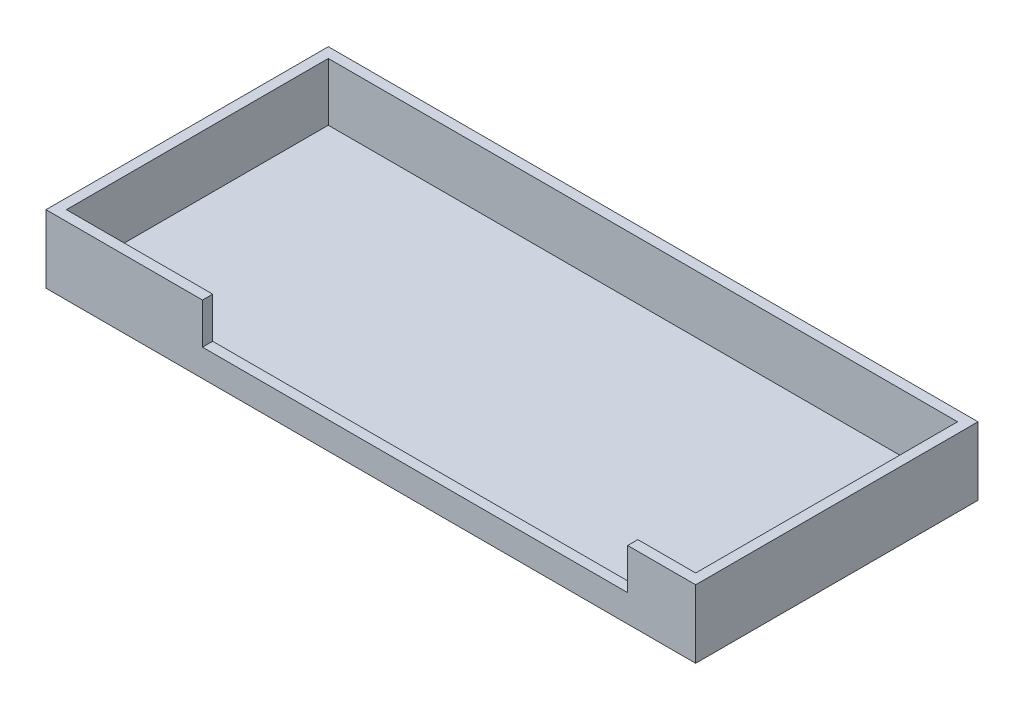
SolidWorks part; units mm, degrees
ref_plane "Front Plane" through (0, 0, 0) normal (0, 0, 1) x (1, 0, 0)
ref_plane "Top Plane" through (0, 0, 0) normal (0, 1, 0) x (1, 0, 0)
ref_plane "Right Plane" through (0, 0, 0) normal (1, 0, 0) x (0, 0, -1)
sketch "Sketch1" plane through (0, 0, 0) normal (0, 1, 0) x (1, 0, 0)
  line L1 (95.5, 41.5) -> (-95.5, 41.5)
  line L2 (95.5, 41.5) -> (95.5, -41.5)
  line L3 (95.5, -41.5) -> (-95.5, -41.5)
  line L4 (-95.5, 41.5) -> (-95.5, -41.5)
  line L5 (95.5, 41.5) -> (-95.5, -41.5) construction
  line L6 (95.5, -41.5) -> (-95.5, 41.5) construction
  point P0 (0, 0)
  dimension "D1" = 191
  dimension "D2" = 83
extrude "Boss-Extrude2" add sketch "Sketch1" along normal blind 20
sketch "Sketch3" plane through (0, 20, 0) normal (0, 1, 0) x (1, 0, 0)
  line L1 (92.5, 38.5) -> (-92.5, 38.5)
  line L2 (92.5, 38.5) -> (92.5, -38.5)
  line L3 (92.5, -38.5) -> (-92.5, -38.5)
  line L4 (-92.5, 38.5) -> (-92.5, -38.5)
  line L5 (92.5, 38.5) -> (-92.5, -38.5) construction
  line L6 (92.5, -38.5) -> (-92.5, 38.5) construction
  point P0 (0, 0)
  dimension "D1" = 185
  dimension "D2" = 77
extrude "Cut-Extrude2" cut sketch "Sketch3" against normal blind 17
sketch "Sketch5" plane through (0, 0, 41.5) normal (0, 0, 1) x (1, 0, 0)
  line L0 (95.5, 20) -> (95.5, 0) construction
  line L1 (75.5, 29.4006) -> (-49.5, 29.4006)
  line L2 (75.5, 29.4006) -> (75.5, 7.9948)
  line L3 (75.5, 7.9948) -> (-49.5, 7.9948)
  line L4 (-49.5, 29.4006) -> (-49.5, 7.9948)
  line L5 (75.5, 29.4006) -> (-49.5, 7.9948) construction
  line L6 (75.5, 7.9948) -> (-49.5, 29.4006) construction
  point P0 (13, 18.6977)
  dimension "D1" = 20
  dimension "D2" = 125
extrude "Cut-Extrude3" cut sketch "Sketch5" against normal blind 17
